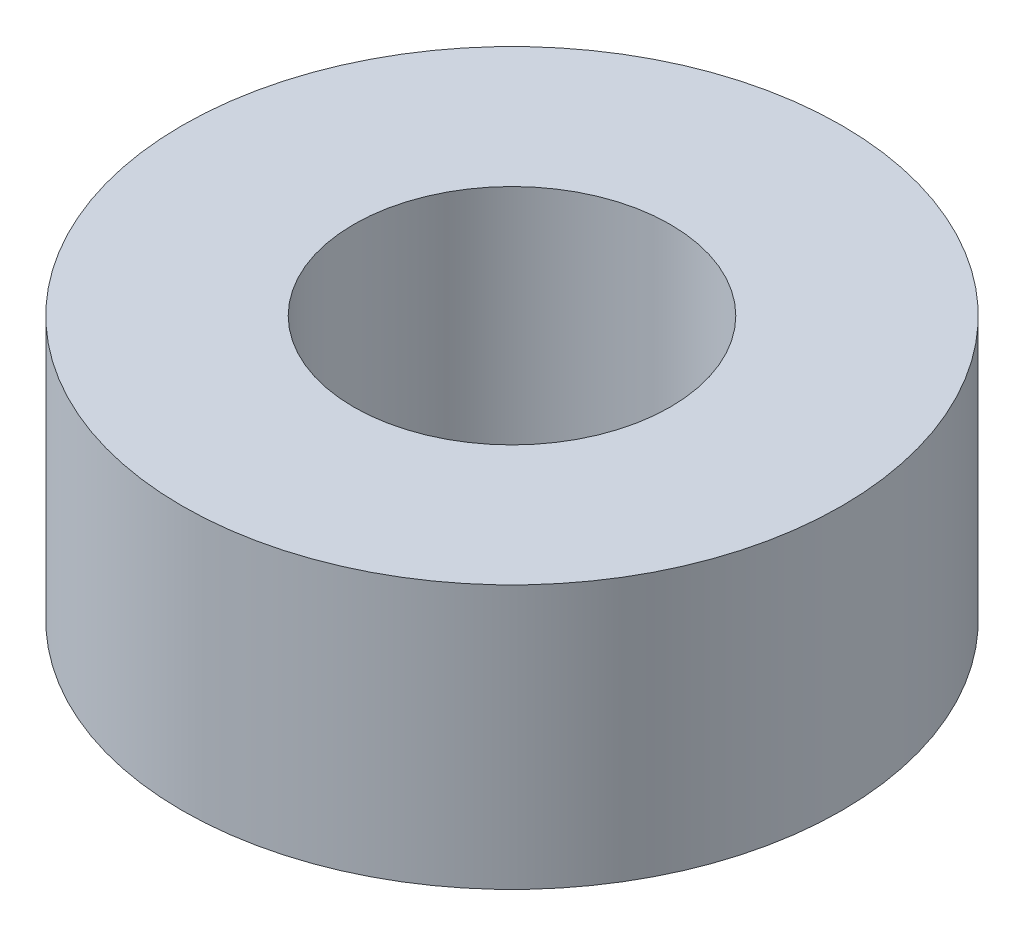
SolidWorks part; units mm, degrees
ref_plane "Front Plane" through (0, 0, 0) normal (0, 0, 1) x (1, 0, 0)
ref_plane "Top Plane" through (0, 0, 0) normal (0, 1, 0) x (1, 0, 0)
ref_plane "Right Plane" through (0, 0, 0) normal (1, 0, 0) x (0, 0, -1)
sketch "Sketch1" plane through (0, 0, 0) normal (0, 1, 0) x (1, 0, 0)
  circle A0 centre (0, 0) radius 6.35
  dimension "D1" = 12.7
extrude "Boss-Extrude1" add sketch "Sketch1" along normal blind 5.08
sketch "Sketch2" plane through (0, 5.08, 0) normal (0, 1, 0) x (1, 0, 0)
  circle A0 centre (0, 0) radius 3.048
  dimension "D1" = 6.096
extrude "Cut-Extrude1" cut sketch "Sketch2" against normal blind 5.08
